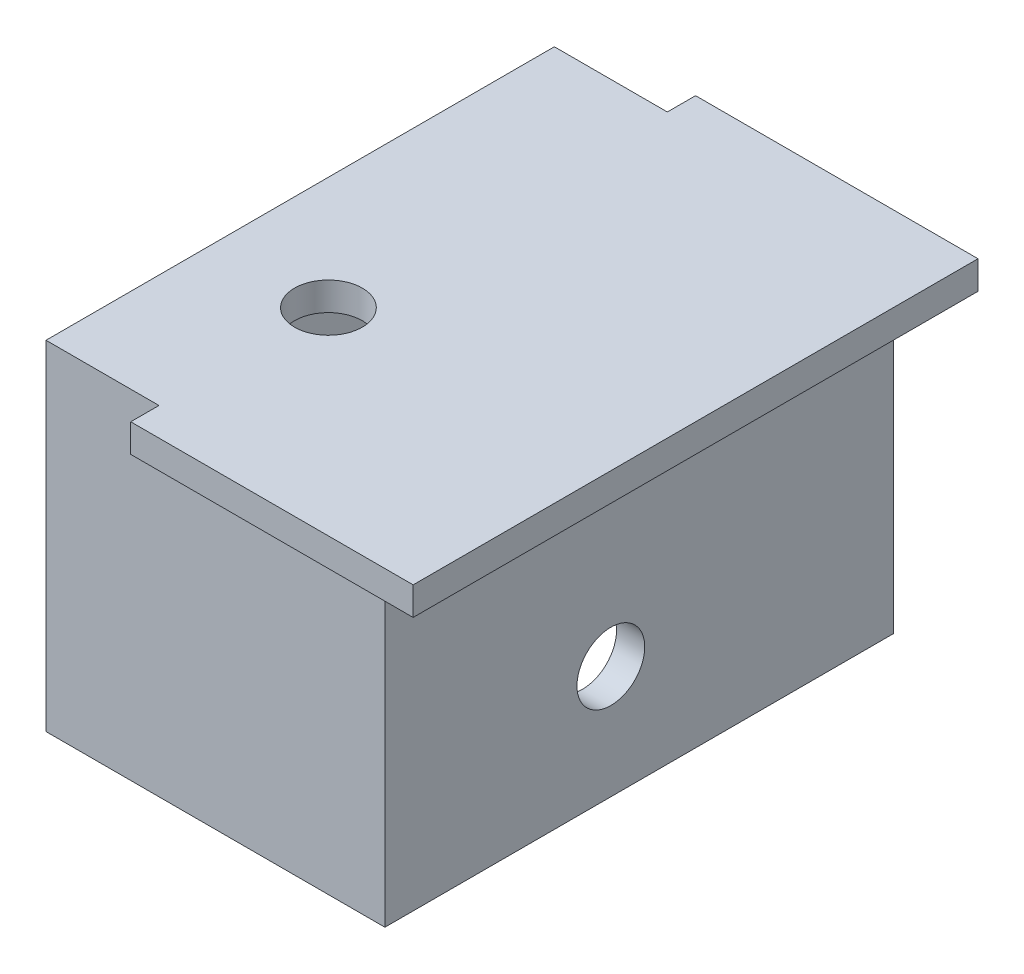
SolidWorks part; units mm, degrees
material "CA"
ref_plane "Front Plane" through (0, 0, 0) normal (0, 0, 1) x (1, 0, 0)
ref_plane "Top Plane" through (0, 0, 0) normal (0, 1, 0) x (1, 0, 0)
ref_plane "Right Plane" through (0, 0, 0) normal (1, 0, 0) x (0, 0, -1)
sketch "Sketch1" plane through (0, 0, 0) normal (0, 0, 1) x (1, 0, 0)
  line L1 (0, 0) -> (-65, 0)
  line L2 (0, 0) -> (0, 5)
  line L3 (0, 5) -> (-65, 5)
  line L6 (-65, 5) -> (-65, 30)
  line L7 (-65, 30) -> (-70, 30)
  line L8 (-70, 0) -> (-70, 30)
  line L10 (-65, 0) -> (-65, -55)
  line L11 (-65, -55) -> (-70, -55)
  line L12 (-70, 0) -> (-70, -55)
  dimension "D1" = 5
  dimension "D2" = 5
  dimension "D3" = 65
  dimension "D4" = 30
  dimension "D5" = 55
extrude "Boss-Extrude1" add sketch "Sketch1" along normal blind 100
sketch "Sketch2" plane through (0, 0, 100) normal (0, 0, 1) x (1, 0, 0)
  line L10 (-65, 0) -> (-70, 0)
  line L11 (-65, 0) -> (-65, -55)
  line L12 (-65, -55) -> (-70, -55)
  line L13 (-70, 0) -> (-70, -55)
extrude "Cut-Extrude2" cut sketch "Sketch2" against normal blind 5
sketch "Sketch3" plane through (0, 0, 0) normal (0, 0, -1) x (-1, 0, 0)
  line L1 (65, 0) -> (70, 0)
  line L2 (65, 0) -> (65, -55)
  line L3 (65, -55) -> (70, -55)
  line L4 (70, 0) -> (70, -55)
extrude "Cut-Extrude3" cut sketch "Sketch3" against normal blind 5
sketch "Sketch4" plane through (0, 0, 100) normal (0, 0, 1) x (1, 0, 0)
  line L0 (-70, 0) -> (0, 0) construction
  line L1 (-65, 5) -> (-50, 5)
  line L2 (-65, 5) -> (-65, 0)
  line L3 (-65, 0) -> (-50, 0)
  line L4 (-50, 5) -> (-50, 0)
  dimension "D1" = 15
extrude "Cut-Extrude4" cut sketch "Sketch4" against normal blind 5
sketch "Sketch5" plane through (0, 0, 0) normal (0, 0, -1) x (-1, 0, 0)
  line L0 (70, 0) -> (0, 0) construction
  line L1 (65, 5) -> (50, 5)
  line L2 (65, 5) -> (65, 0)
  line L3 (65, 0) -> (50, 0)
  line L4 (50, 5) -> (50, 0)
  dimension "D1" = 15
extrude "Cut-Extrude5" cut sketch "Sketch5" against normal blind 5
sketch "Sketch6" plane through (0, 5, 0) normal (0, 1, 0) x (1, 0, 0)
  line L1 (-65, -95) -> (-65, -5) construction
  line L2 (0, 0) -> (-50, 0) construction
  circle A0 centre (-50, -65) radius 6
  dimension "D1" = 12
  dimension "D2" = 65
  dimension "D3" = 15
extrude "Cut-Extrude6" cut sketch "Sketch6" against normal blind 10
sketch "Sketch7" plane through (0, 0, 0) normal (0, -1, 0) x (1, 0, 0)
  line L0 (-50, 0) -> (0, 0) construction
  line L1 (-10, 5) -> (-15, 5)
  line L2 (-10, 5) -> (-10, 95)
  line L3 (-10, 95) -> (-15, 95)
  line L4 (-15, 5) -> (-15, 95)
  line L5 (-50, 100) -> (0, 100) construction
  line L6 (0, 100) -> (0, 0) construction
  dimension "D1" = 5
  dimension "D2" = 5
  dimension "D3" = 5
  dimension "D4" = 10
extrude "Boss-Extrude2" add sketch "Sketch7" along normal blind 55
sketch "Sketch8" plane through (-70, 0, 0) normal (-1, 0, 0) x (0, 0, 1)
  line L0 (95, 0) -> (95, -55) construction
  line L3 (95, -55) -> (5, -55) construction
  circle A0 centre (55, -35) radius 6
  dimension "D1" = 40
  dimension "D2" = 20
extrude "Cut-Extrude7" cut sketch "Sketch8" against normal blind 80
sketch "Sketch9" plane through (0, 0, 100) normal (0, 0, 1) x (1, 0, 0)
  line L0 (-65, 0) -> (-65, 30) construction
  line L1 (-70, 30) -> (-65, 30)
  line L2 (-70, 30) -> (-70, 5)
  line L3 (-70, 5) -> (-65, 5)
  line L4 (-65, 30) -> (-65, 5)
  dimension "D1" = 25
extrude "Cut-Extrude8" cut sketch "Sketch9" against normal blind 100
sketch "Sketch10" plane through (0, 0, 100) normal (0, 0, 1) x (1, 0, 0)
  line L1 (-70, 0) -> (-65, 0)
  line L2 (-70, 0) -> (-70, 5)
  line L3 (-70, 5) -> (-65, 5)
  line L4 (-65, 0) -> (-65, 5)
extrude "Cut-Extrude9" cut sketch "Sketch10" against normal blind 5
sketch "Sketch11" plane through (0, 0, 0) normal (0, 0, -1) x (-1, 0, 0)
  line L1 (65, 5) -> (70, 5)
  line L2 (65, 5) -> (65, 0)
  line L3 (65, 0) -> (70, 0)
  line L4 (70, 5) -> (70, 0)
extrude "Cut-Extrude10" cut sketch "Sketch11" against normal blind 5
sketch "Sketch12" plane through (0, 0, 0) normal (0, -1, 0) x (1, 0, 0)
  line L0 (-65, 95) -> (-65, 5) construction
  line L1 (-15, 5) -> (-65, 5)
  line L2 (-15, 5) -> (-15, 10)
  line L3 (-15, 10) -> (-65, 10)
  line L4 (-65, 5) -> (-65, 10)
  line L5 (-15, 95) -> (-15, 5) construction
  line L6 (-65, 95) -> (-15, 95)
  line L7 (-65, 95) -> (-65, 90)
  line L8 (-65, 90) -> (-15, 90)
  line L9 (-15, 95) -> (-15, 90)
  dimension "D1" = 5
  dimension "D2" = 5
extrude "Boss-Extrude3" add sketch "Sketch12" along normal blind 55
